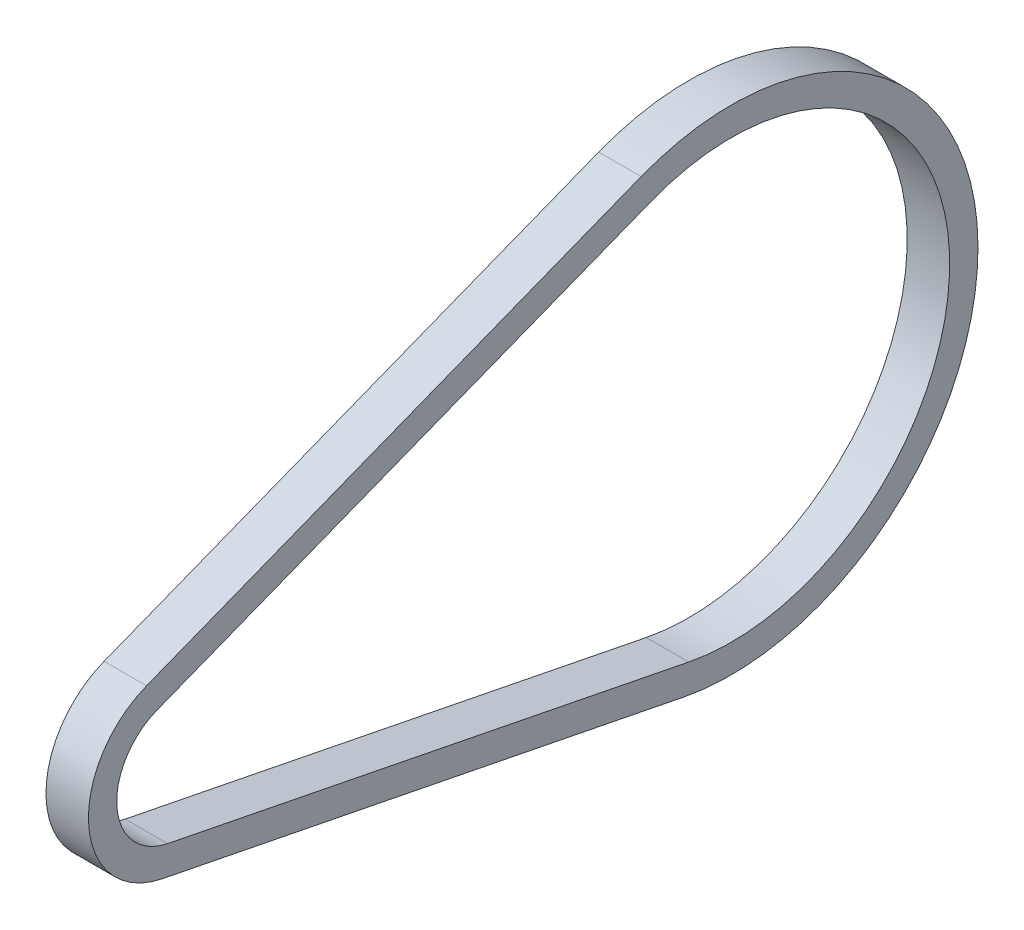
SolidWorks part; units mm, degrees
ref_plane "Front Plane" through (0, 0, 0) normal (0, 0, 1) x (1, 0, 0)
ref_plane "Top Plane" through (0, 0, 0) normal (0, 1, 0) x (1, 0, 0)
ref_plane "Right Plane" through (0, 0, 0) normal (1, 0, 0) x (0, 0, -1)
ref_plane "Plane1" through (110.25, 0, 0) normal (-1, 0, 0) x (0, 0, 1)
sketch "Sketch1" plane through (110.25, 0, 0) normal (-1, 0, 0) x (0, 0, 1)
  line L0 (-789.3664, 298.5688) -> (-611.8751, 229.0504)
  line L1 (-616.6024, 175.9673) -> (-803.5849, 138.9066)
  circle A0 centre (-819.8197, 220.8166) radius 83.5034 construction
  arc A1 (-789.3664, 298.5688) -> (-803.5849, 138.9066) centre (-819.8197, 220.8166) ccw
  arc A2 (-611.8751, 229.0504) -> (-616.6024, 175.9673) centre (-622, 203.2) cw
  arc A3 (-577.9962, 240.5996) -> (-577.9962, 165.8004) centre (-622, 203.2) ccw construction
  arc A4 (-594.2375, 203.2) -> (-630.5791, 229.6037) centre (-622, 203.2) ccw construction
  point P2 (-611.6573, 231.3607)
  point P11 (-611.8492, 229.0402)
extrude "Extrude-Thin1" add sketch "Sketch1" along normal mid plane 15.24 thin thin type mid plane wall 10.16
